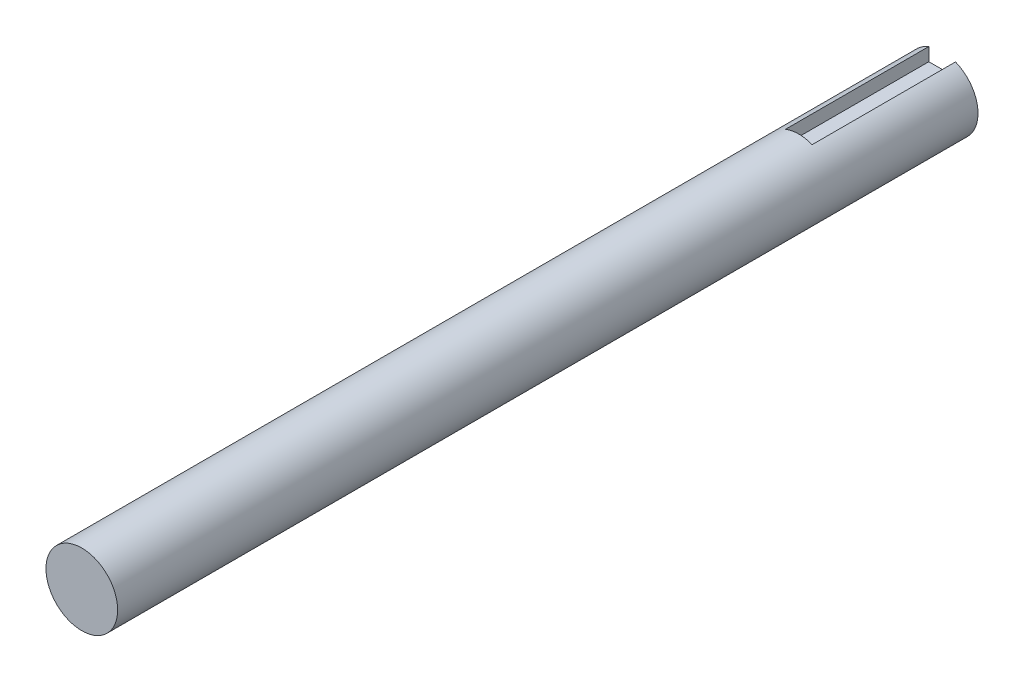
SolidWorks part; units mm, degrees
ref_plane "Front Plane" through (0, 0, 0) normal (0, 0, 1) x (1, 0, 0)
ref_plane "Top Plane" through (0, 0, 0) normal (0, 1, 0) x (1, 0, 0)
ref_plane "Right Plane" through (0, 0, 0) normal (1, 0, 0) x (0, 0, -1)
sketch "Sketch1" plane through (0, 0, 0) normal (0, 1, 0) x (0, 0, -1)
  line L0 (-38.1, 0) -> (38.1, 0)
  line L1 (0, 3.175) -> (0, -3.175)
  line L2 (25.4, 1.1811) -> (25.4, -1.1811)
  line L3 (25.4, 1.1811) -> (26.5684, 1.1811)
  point P4 (0, 0)
  point P8 (0, 0)
  point P14 (25.4, 0)
  dimension "Length" = 76.2
  dimension "Diameter" = 6.35
  dimension "Keyway Depth" = 1.1684
  dimension "Keyway Length" = 12.7
  dimension "Keyway Width" = 2.3622
sketch "Sketch2" plane through (0, 0, 0) normal (0, 0, 1) x (1, 0, 0)
  circle A0 centre (0, 0) radius 3.175
extrude "Boss-Extrude1" add sketch "Sketch2" along normal up to vertex (38.1 mm away) and the other way up to vertex (38.1 mm away) up to point (0, 0, 38.1) other way up to point (0, 0, -38.1)
sketch "Sketch3" plane through (0, 0, -38.1) normal (0, 0, -1) x (-1, 0, 0)
  line L3 (1.1811, 2.9471) -> (1.1811, 1.7787)
  line L4 (1.1811, 1.7787) -> (-1.1811, 1.7787)
  line L5 (-1.1811, 1.7787) -> (-1.1811, 2.9471)
  circle A2 centre (0, 0) radius 3.175 construction
  arc A3 (1.1811, 2.9471) -> (-1.1811, 2.9471) centre (0, 0) ccw
  point P6 (0, 1.7787)
  dimension "D1" = 1.1684
extrude "Cut-Extrude1" cut sketch "Sketch3" against normal up to vertex (12.7 mm away) up to point (-1.1811, 0, -25.4)
sketch "Sketch4" plane through (0, 0, 0) normal (1, 0, 0) x (0, 0, -1)
  line L0 (-38.1, 0) -> (38.1, 0) construction
  point P0 (-22.86, 0)
  point P1 (22.86, 0)
  point P2 (-17.78, 0)
  point P3 (20.5024, 0)
  dimension "D1" = 15.24
  dimension "D2" = 15.24
  dimension "D3" = 17.5976
  dimension "D4" = 20.32
equation "\"D1@Sketch4\"=\"Length@Sketch1\"*.2"
equation "\"D2@Sketch4\"=\"D1@Sketch4\""
equation "\"D3@Sketch4\"=\"D1@Sketch4\"/(2*tan(.5236*180/pi))*4/3"
equation "\"D4@Sketch4\"=4/3*\"D2@Sketch4\""
equation "\"D1@Sketch3\"=\"Keyway Depth@Sketch1\""
